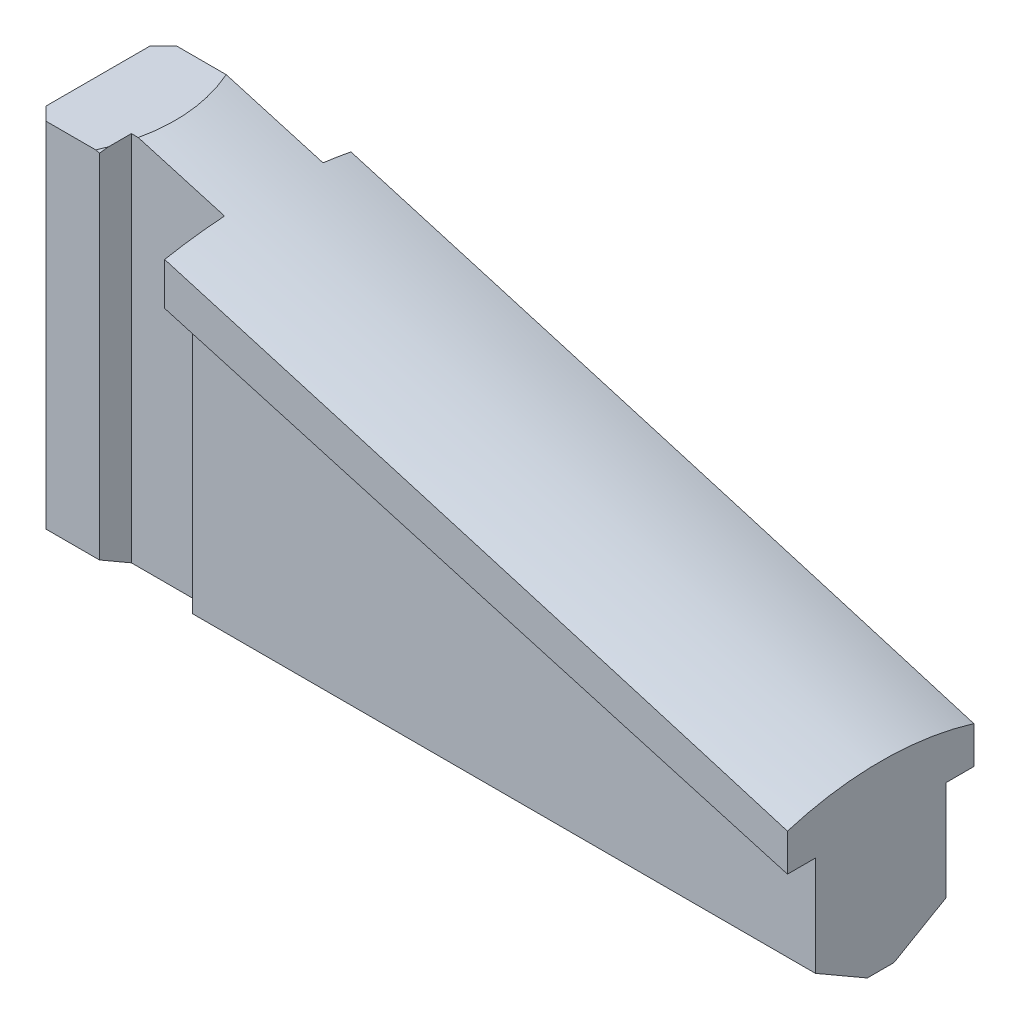
SolidWorks part; units mm, degrees
material "1.7223 (41CrMo4)"
ref_plane "Plan de face" through (0, 0, 0) normal (0, 0, 1) x (1, 0, 0)
ref_plane "Plan de dessus" through (0, 0, 0) normal (0, 1, 0) x (1, 0, 0)
ref_plane "Plan de droite" through (0, 0, 0) normal (1, 0, 0) x (0, 0, -1)
sketch "Esquisse1" plane through (0, 0, 0) normal (0, 0, 1) x (1, 0, 0)
  line L0 (0, 0) -> (-10.7824, 0) construction
  line L1 (0, 20.4303) -> (0, 0)
  line L13 (0, 20.4303) -> (29.4, 12)
  line L14 (29.4, 12) -> (29.4, 0)
  line L15 (29.4, 0) -> (0, 0)
  dimension "D2" = 16
  dimension "D3" = 24
  dimension "D14" = 29.4
revolve "Révolution1" add sketch "Esquisse1" angle 180 mid plane about L0
sketch "Esquisse3" plane through (29.4, 0, 0) normal (1, 0, 0) x (0, 0, -1)
  line L0 (-3.5, 6.9321) -> (-0.5, 5.2)
  line L1 (-3.5, 19.6) -> (3.5, 19.6)
  line L2 (-3.5, 19.6) -> (-3.5, 6.9321)
  line L3 (-0.5, 5.2) -> (0.5, 5.2)
  line L4 (3.5, 19.6) -> (3.5, 6.9321)
  line L5 (0.5, 5.2) -> (3.5, 6.9321)
  line L6 (0, 12) -> (0, 5.2) construction
  arc A0 (12, 0) -> (-12, 0) centre (0, 0) ccw construction
  dimension "D1" = 1
  dimension "D2" = 6.8
  dimension "D3" = 14.4
  dimension "D4" = 7
  dimension "D5" = 120
extrude "Enlèv. mat.-Extru.1" cut sketch "Esquisse3" against normal through all flip side to cut
sketch "Esquisse4" plane through (29.4, 0, 0) normal (1, 0, 0) x (0, 0, -1)
  line L0 (3.5, 6.9321) -> (3.5, 11.4782) construction
  line L1 (3.5, 10.0782) -> (2.45, 10.0782)
  line L2 (3.5, 10.0782) -> (3.5, -19.9218)
  line L3 (3.5, -19.9218) -> (2.45, -19.9218)
  line L4 (2.45, 10.0782) -> (2.45, -19.9218)
  line L5 (-3.5, 11.4782) -> (-3.5, 6.9321) construction
  line L6 (-3.5, 10.0782) -> (-2.45, 10.0782)
  line L7 (-3.5, 10.0782) -> (-3.5, -19.9218)
  line L8 (-3.5, -19.9218) -> (-2.45, -19.9218)
  line L9 (-2.45, 10.0782) -> (-2.45, -19.9218)
  dimension "D1" = 4.9
  dimension "D2" = 1.4
  dimension "D3" = 30
sketch "Esquisse5" plane through (0, 0, 0) normal (0, 0, -1) x (-1, 0, 0)
  line L0 (-29.4, 10.0782) -> (0, 18.5086)
  line L3 (-2.8957, 19.6) -> (-29.4, 12) construction
  line L4 (0, 19.6) -> (0, 6.9321) construction
  line L5 (0, 5.2) -> (-29.4, 5.2) construction
  dimension "D1" = 16
sweep "Enlèvement de matière-Balayage1" cut profiles "Esquisse4" path "Esquisse5"
sketch "Esquisse6" plane through (0, 19.6, 0) normal (0, 1, 0) x (-1, 0, 0)
  line L0 (0, -3.5) -> (-1.8144, -3.5) construction
  line L1 (0, -3.5) -> (-6, -3.5)
  line L2 (0, -3.5) -> (0, -2.45)
  line L3 (0, -2.45) -> (-6, -2.45)
  line L4 (-6, -3.5) -> (-6, -2.45)
  line L5 (0, -2.45) -> (-29.4, -2.45) construction
  line L6 (0, 2.45) -> (-29.4, 2.45) construction
  line L7 (0, 3.5) -> (-6, 3.5)
  line L8 (0, 3.5) -> (0, 2.45)
  line L9 (0, 2.45) -> (-2.5, 2.45)
  line L10 (-6, 3.5) -> (-6, 2.45)
  line L11 (0, -3.5) -> (0, 3.5) construction
  line L12 (-2.5, 2.45) -> (-2.5, 1.25)
  line L13 (-2.5, 1.25) -> (-6, 1.25)
  line L14 (-6, 1.25) -> (-6, 2.45)
  dimension "D1" = 6
  dimension "D2" = 3.5
  dimension "D3" = 3.7
extrude "Enlèv. mat.-Extru.2" cut sketch "Esquisse6" against normal through all
chamfer "Chanfrein1" distance 0.5 angle 45 2 edges at (0, 12.9629, -2.45) (0, 12.9629, 2.45)
